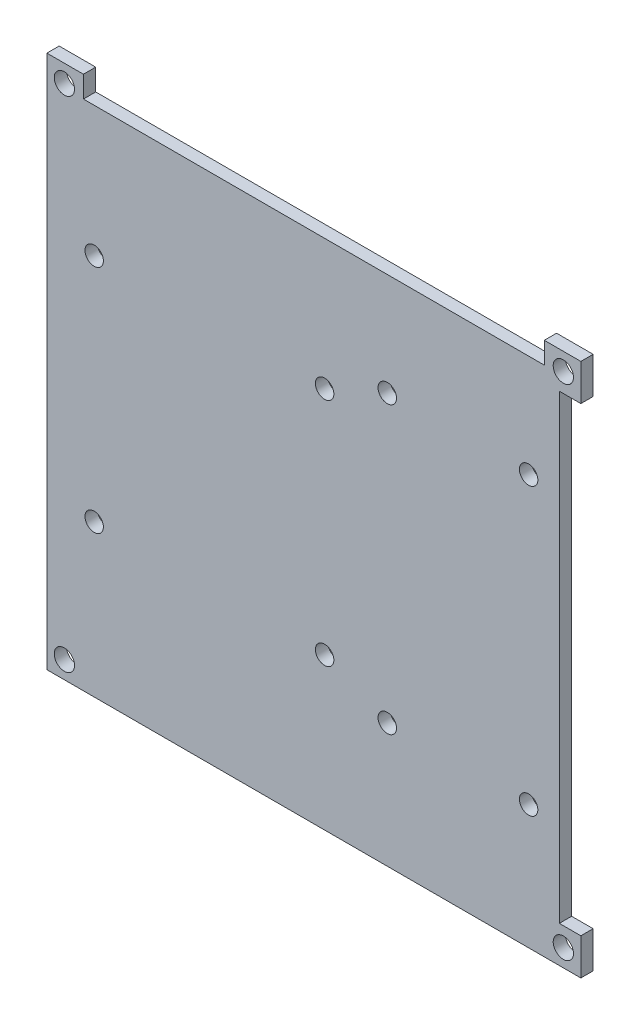
SolidWorks part; units mm, degrees
ref_plane "Front Plane" through (0, 0, 0) normal (1, 0, 0) x (0, 1, 0)
ref_plane "Top Plane" through (0, 0, 0) normal (0, 0, 1) x (0, 1, 0)
ref_plane "Right Plane" through (0, 0, 0) normal (0, 1, 0) x (-1, 0, 0)
sketch "Sketch1" plane through (0, 0, 0) normal (0, 0, 1) x (0, 1, 0)
  line L1 (0, 0) -> (86.9, 0)
  line L2 (0, 0) -> (0, 86.9)
  line L3 (0, 86.9) -> (86.9, 86.9)
  line L4 (86.9, 0) -> (86.9, 86.9)
  dimension "D1" = 86.9
  dimension "D2" = 86.9
extrude "Boss-Extrude1" add sketch "Sketch1" along normal blind 2 contours L3 L4 L1 L2
sketch "Sketch2" plane through (0, 0, 2) normal (0, 0, 1) x (1, 0, 0)
  line L0 (0, 0) -> (-86.9, 0) construction
  line L1 (-84.05, 84.05) -> (-2.85, 84.05) construction
  line L2 (-84.05, 84.05) -> (-84.05, 2.85) construction
  line L3 (-84.05, 2.85) -> (-2.85, 2.85) construction
  line L4 (-2.85, 84.05) -> (-2.85, 2.85) construction
  line L5 (0, 0) -> (0, 86.9) construction
  circle A0 centre (-84.05, 2.85) radius 1.65
  circle A1 centre (-2.85, 2.85) radius 1.65
  circle A2 centre (-2.85, 84.05) radius 1.65
  circle A3 centre (-84.05, 84.05) radius 1.65
  dimension "D3" = 3.3
  dimension "D1" = 81.2
  dimension "D2" = 81.2
  dimension "D4" = 2.85
  dimension "D5" = 2.85
extrude "Cut-Extrude3" cut sketch "Sketch2" against normal through all
sketch "Sketch3" plane through (0, 0, 2) normal (0, 0, 1) x (1, 0, 0)
  line L0 (-79.2, 62.2) -> (-41.7, 24.7) construction
  line L1 (-79.2, 62.2) -> (-41.7, 62.2) construction
  line L2 (-79.2, 62.2) -> (-79.2, 24.7) construction
  line L3 (-79.2, 24.7) -> (-41.7, 24.7) construction
  line L4 (-41.7, 62.2) -> (-41.7, 24.7) construction
  line L5 (0, 0) -> (0, 86.9) construction
  line L6 (0, 0) -> (-86.9, 0) construction
  line L7 (-79.2, 24.7) -> (-41.7, 62.2) construction
  circle A0 centre (-79.2, 62.2) radius 1.5
  circle A1 centre (-41.7, 62.2) radius 1.5
  circle A2 centre (-41.7, 24.7) radius 1.5
  circle A3 centre (-79.2, 24.7) radius 1.5
  point P1 (-60.45, 43.45)
  dimension "D2" = 3
  dimension "D1" = 37.5
  dimension "D3" = 60.45
  dimension "D4" = 43.45
extrude "Cut-Extrude4" cut sketch "Sketch3" against normal blind 10
sketch "Sketch4" plane through (0, 0, 2) normal (0, 0, 1) x (1, 0, 0)
  line L0 (-31.5, 66.7) -> (-8.5, 20.2) construction
  line L1 (-31.5, 20.2) -> (-8.5, 20.2) construction
  line L2 (-31.5, 20.2) -> (-31.5, 66.7) construction
  line L3 (-31.5, 66.7) -> (-8.5, 66.7) construction
  line L4 (-8.5, 20.2) -> (-8.5, 66.7) construction
  line L5 (-31.5, 20.2) -> (-8.5, 66.7) construction
  line L6 (0, 0) -> (0, 86.9) construction
  line L8 (0, 0) -> (-86.9, 0) construction
  circle A0 centre (-31.5, 66.7) radius 1.5
  circle A1 centre (-8.5, 66.7) radius 1.5
  circle A2 centre (-8.5, 20.2) radius 1.5
  circle A3 centre (-31.5, 20.2) radius 1.5
  point P10 (-20, 43.45)
  dimension "D3" = 3
  dimension "D1" = 46.5
  dimension "D2" = 23
  dimension "D4" = 20
  dimension "D5" = 43.45
extrude "Cut-Extrude5" cut sketch "Sketch4" against normal blind 10
sketch "Sketch5" plane through (0, 0, 2) normal (0, 0, 1) x (1, 0, 0)
  line L0 (0, 0) -> (0, 86.9) construction
  line L1 (0, 80.95) -> (-3.5, 80.95)
  line L2 (0, 80.95) -> (0, 5.95)
  line L3 (0, 5.95) -> (-3.5, 5.95)
  line L4 (-3.5, 80.95) -> (-3.5, 5.95)
  line L5 (0, 86.9) -> (-86.9, 0) construction
  line L6 (-80.95, 86.9) -> (-80.95, 83.4)
  line L7 (-5.95, 83.4) -> (-80.95, 83.4)
  line L8 (-5.95, 86.9) -> (-5.95, 83.4)
  line L9 (-5.95, 86.9) -> (-80.95, 86.9)
  point P6 (0, 43.45)
  point P7 (0, 43.45)
  dimension "D1" = 3.5
  dimension "D2" = 75
extrude "Cut-Extrude6" cut sketch "Sketch5" against normal through all
